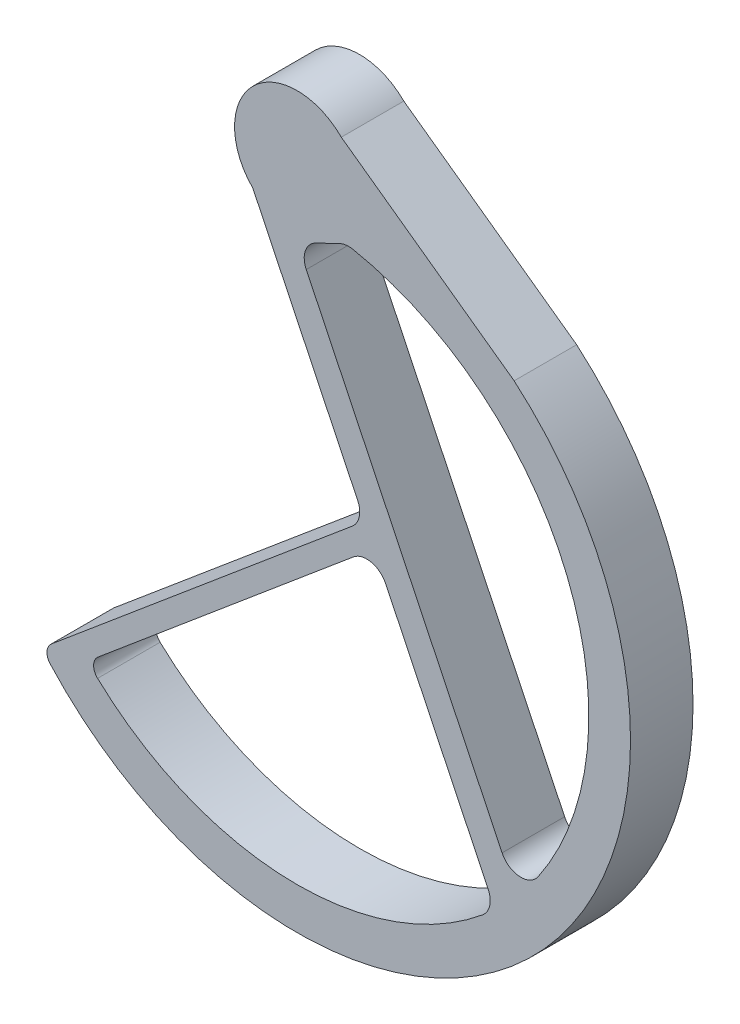
SolidWorks part; units mm, degrees
material "ABS"
ref_plane "正面" through (0, 0, 0) normal (0, 0, 1) x (1, 0, 0)
ref_plane "平面" through (0, 0, 0) normal (0, 1, 0) x (1, 0, 0)
ref_plane "右側面" through (0, 0, 0) normal (1, 0, 0) x (0, 0, -1)
sketch "ｽｹｯﾁ4" plane through (0, 0, 0) normal (0, 0, 1) x (1, 0, 0)
  line L0 (0, 0.7897) -> (0, 0)
  line L1 (-53.6231, -124.9951) -> (-58.9406, -129.4571)
  line L3 (-10.6066, -10.6066) -> (14.5363, -62.8896)
  line L4 (-53.6231, -124.9951) -> (13.2442, -68.8868)
  line L5 (21.2324, -76.8138) -> (45.8448, -127.9938)
  line L6 (10.6066, 10.6066) -> (52.0762, -19.2705)
  line L7 (-58.0696, -135.2532) -> (-57.9498, -135.1527)
  line L8 (-47.7477, -126.5866) -> (13.5112, -75.1515)
  arc A1 (-59.2335, -133.7716) -> (52.0762, -19.2705) centre (0, -80) ccw
  arc A2 (-47.8702, -131.073) -> (44.5187, -134.0193) centre (0, -80) ccw
  arc A3 (10.6066, 10.6066) -> (-10.6066, -10.6066) centre (0, 0) ccw
  arc A4 (-59.2335, -133.7716) -> (-58.9406, -129.4571) centre (-57.0123, -131.7552) cw
  arc A5 (-47.8702, -131.073) -> (-47.7477, -126.5866) centre (-45.8186, -128.8841) cw
  arc A6 (13.5112, -75.1515) -> (21.2324, -76.8138) centre (16.7264, -78.9807) cw
  arc A7 (13.2442, -68.8868) -> (14.5363, -62.8896) centre (10.0302, -65.0566) ccw
  arc A8 (45.8448, -127.9938) -> (44.5187, -134.0193) centre (41.3388, -130.1608) cw
  point P18 (-61.2836, -131.423)
  point P21 (-50.2744, -128.7081)
  point P24 (18.4421, -71.0114)
  dimension "D3" = 140
  dimension "D4" = 30
  dimension "D5" = 5
  dimension "D6" = 3
  dimension "D7" = 3
  dimension "D8" = 5
  dimension "D9" = 5
  dimension "D10" = 5
  dimension "D2" = 5
extrude "ﾎﾞｽ - 押し出し1" add sketch "ｽｹｯﾁ4" along normal blind 15
sketch "ｽｹｯﾁ6" plane through (0, 0, 15) normal (0, 0, 1) x (1, 0, 0)
  line L6 (49.1896, -118.7973) -> (2.2018, -21.089)
  line L7 (6.4834, -13.4819) -> (4.5408, -14.416)
  line L8 (6.4834, -13.4819) -> (10.2197, -11.6851)
  arc A0 (57.8261, -119.448) -> (13.3394, -11.2828) centre (0, -80) ccw
  arc A1 (2.2018, -21.089) -> (4.5408, -14.416) centre (6.7078, -18.9221) cw
  arc A2 (13.3394, -11.2828) -> (10.2197, -11.6851) centre (12.3866, -16.1911) ccw
  arc A3 (57.8261, -119.448) -> (49.1896, -118.7973) centre (53.6956, -116.6303) cw
  point P7 (0.0348, -16.583)
  point P14 (52.6925, -126.0814)
  dimension "D3" = 121.502
  dimension "D4" = 70
  dimension "D1" = 5
  dimension "D2" = 5
  dimension "D5" = 5
  dimension "D6" = 90
extrude "ｶｯﾄ - 押し出し1" cut sketch "ｽｹｯﾁ6" against normal blind 15
sketch "ｽｹｯﾁ8" plane through (0, 0, 0) normal (0, 0, -1) x (-1, 0, 0)
  circle A0 centre (0, 0) radius 10.1
extrude "ｶｯﾄ - 押し出し3" cut sketch "ｽｹｯﾁ8" against normal blind 2
